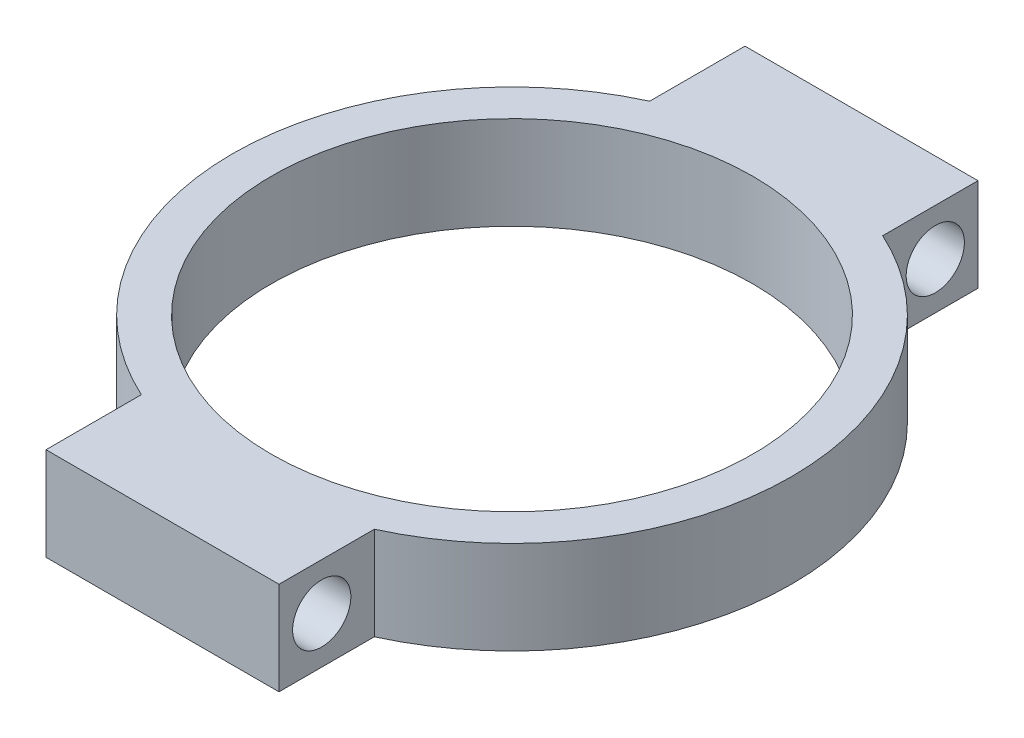
SolidWorks part; units mm, degrees
material "Cast Stainless Steel"
ref_plane "Front Plane" through (0, 0, 0) normal (0, 0, 1) x (1, 0, 0)
ref_plane "Top Plane" through (0, 0, 0) normal (0, 1, 0) x (1, 0, 0)
ref_plane "Right Plane" through (0, 0, 0) normal (1, 0, 0) x (0, 0, -1)
sketch "Sketch1" plane through (0, 0, 0) normal (0, 1, 0) x (1, 0, 0)
  line L0 (-19.05, 57.15) -> (19.05, 57.15)
  line L1 (-19.05, -57.15) -> (19.05, -57.15)
  line L4 (-19.05, 57.15) -> (-19.05, 41.5622)
  line L6 (0, 64.6445) -> (0, -62.188) construction
  line L9 (19.05, -57.15) -> (19.05, -41.5622)
  line L10 (19.05, 57.15) -> (19.05, 41.5622)
  line L13 (-19.05, -57.15) -> (-19.05, -41.5622)
  line L17 (0, 45.72) -> (0, -45.72) construction
  circle A0 centre (0, 0) radius 39.37
  arc A1 (-19.05, 41.5622) -> (-19.05, -41.5622) centre (0, 0) ccw
  arc A3 (19.05, 41.5622) -> (19.05, -41.5622) centre (0, 0) cw
  dimension "D1" = 78.74
  dimension "D2" = 0
  dimension "D3" = 39.37
  dimension "D5" = 6.35
  dimension "D4" = 38.1
extrude "Boss-Extrude1" add sketch "Sketch1" along normal blind 15.24
sketch "Sketch2" plane through (-19.05, 0, 0) normal (-1, 0, 0) x (0, 0, 1)
  line L1 (57.15, 7.62) -> (-57.15, 7.62) construction
  line L3 (-57.15, 15.24) -> (-57.15, 0) construction
  line L4 (57.15, 15.24) -> (57.15, 0) construction
  circle A0 centre (50.165, 7.62) radius 4.7625
  circle A1 centre (-50.165, 7.62) radius 4.7625
  dimension "D1" = 9.525
  dimension "D2" = 6.985
  dimension "D3" = 6.985
extrude "Cut-Extrude1" cut sketch "Sketch2" against normal through all contours A0 L1 | L1 A0 | A1
ref_plane "Plane1" through (0, 0, 0) normal (-1, 0, 0) x (0, 0, 1)
